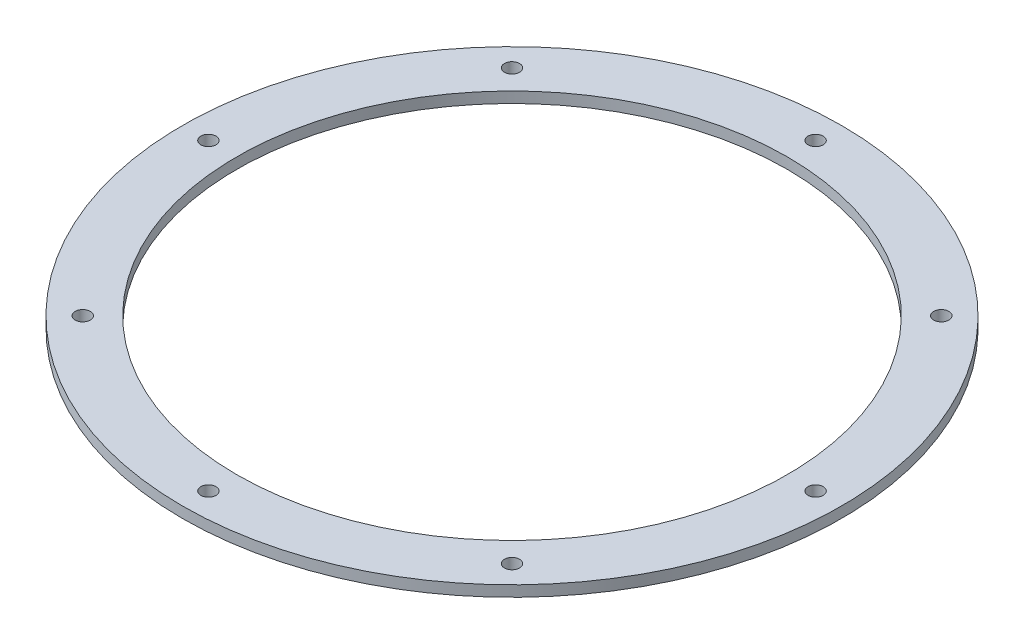
SolidWorks part; units mm, degrees
material "Thornel Mat VMA"
ref_plane "前视基准面" through (0, 0, 0) normal (0, 0, 1) x (1, 0, 0)
ref_plane "上视基准面" through (0, 0, 0) normal (0, 1, 0) x (1, 0, 0)
ref_plane "右视基准面" through (0, 0, 0) normal (1, 0, 0) x (0, 0, -1)
other "Configuration Table"
sketch "草图1" plane through (0, 0, 0) normal (0, 0, 1) x (1, 0, 0)
  line L0 (0, 0) -> (0, 37.8666) construction
  line L2 (76.08, 3) -> (91.08, 3)
  line L3 (76.08, 3) -> (76.08, 0)
  line L4 (76.08, 0) -> (91.08, 0)
  line L5 (91.08, 3) -> (91.08, 0)
  dimension "D1" = 3
  dimension "D2" = 15
  dimension "D3" = 91.08
revolve "旋转1" add sketch "草图1" angle 360 about L0
sketch "草图2" plane through (0, 3, 0) normal (0, 1, 0) x (1, 0, 0)
  circle A0 centre (0, 0) radius 83.9 construction
  circle A1 centre (-83.9, 0) radius 2.1
  circle A2 centre (-59.3263, 59.3263) radius 2.1
  circle A3 centre (0, 83.9) radius 2.1
  circle A4 centre (59.3263, 59.3263) radius 2.1
  circle A5 centre (83.9, 0) radius 2.1
  circle A6 centre (59.3263, -59.3263) radius 2.1
  circle A7 centre (0, -83.9) radius 2.1
  circle A8 centre (-59.3263, -59.3263) radius 2.1
  point P22 (0, 0)
  dimension "D1" = 4.2
  dimension "D3" = 167.8
  dimension "D2" = 8
extrude "切除-拉伸1" cut sketch "草图2" against normal blind 10
